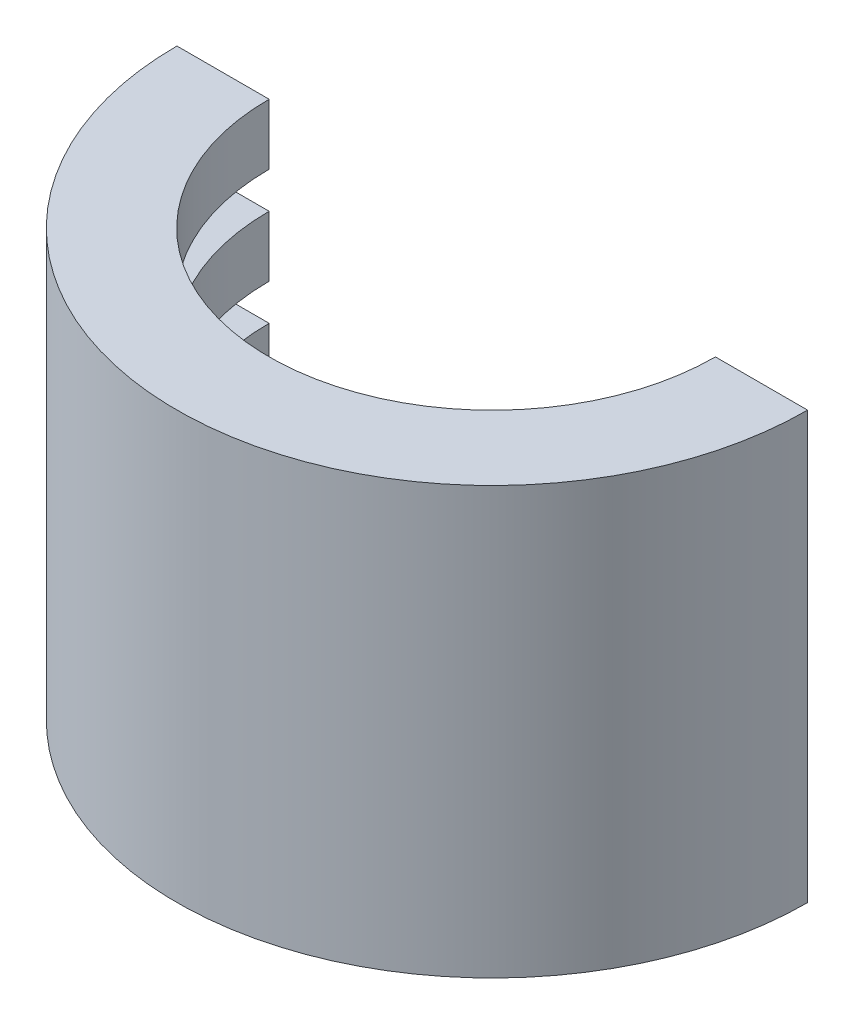
SolidWorks part; units mm, degrees
ref_plane "前视基准面" through (0, 0, 0) normal (0, 0, 1) x (1, 0, 0)
ref_plane "上视基准面" through (0, 0, 0) normal (0, 1, 0) x (1, 0, 0)
ref_plane "右视基准面" through (0, 0, 0) normal (1, 0, 0) x (0, 0, -1)
sketch "草图1" plane through (0, 0, 0) normal (0, 0, 1) x (1, 0, 0)
  line L0 (0, 0) -> (0, 2)
  line L2 (1.5, 2) -> (1.5, 0)
  line L3 (1.5, 0) -> (11, 0)
  line L6 (13, 16) -> (9.2, 16)
  line L7 (9.2, 1.5) -> (9.2, 4)
  line L8 (9.2, 4) -> (11, 4)
  line L9 (11, 4) -> (11, 5.5)
  line L10 (11, 5.5) -> (9.2, 5.5)
  line L11 (9.2, 5.5) -> (9.2, 8)
  line L12 (9.2, 8) -> (11, 8)
  line L13 (11, 8) -> (11, 9.5)
  line L14 (11, 9.5) -> (9.2, 9.5)
  line L15 (9.2, 9.5) -> (9.2, 12)
  line L16 (11, 0) -> (11, 1.5)
  line L17 (9.2, 12) -> (11, 12)
  line L18 (9.2, 1.5) -> (11, 1.5)
  line L19 (11, 12) -> (11, 13.5)
  line L20 (11, 13.5) -> (9.2, 13.5)
  line L21 (9.2, 13.5) -> (9.2, 16)
  line L22 (0, 0) -> (0, -1.5846)
  line L23 (0, -1.5846) -> (13, -1.5846)
  line L25 (13, 16) -> (13, -1.5846)
  line L26 (0, 2) -> (1.5, 2)
  line L27 (7.2, 1.5) -> (7.2, 16)
  line L28 (7.2, 16) -> (13, 16)
  line L29 (13, 18) -> (0, 18)
  line L30 (0, 18) -> (0, 2)
  line L31 (1.5, 2) -> (1.5, 1.5)
  line L32 (0, 2) -> (1.6, 2)
  line L33 (13, 16) -> (13, 18)
  line L34 (1.6, 2) -> (1.6, 1.5)
  line L35 (1.6, 1.5) -> (7.2, 1.5)
  dimension "D1" = 2.5
  dimension "D2" = 1.5
  dimension "D3" = 2
  dimension "D4" = 11
  dimension "D5" = 1.5
  dimension "D6" = 2.5
  dimension "D7" = 1.5
  dimension "D8" = 2.5
  dimension "D9" = 1.5
  dimension "D10" = 1.5
  dimension "D11" = 2.5
  dimension "D12" = 13
  dimension "D13" = 2
  dimension "D14" = 5.7
  dimension "D15" = 1.8
  dimension "D16" = 1.8
  dimension "D17" = 1.8
  dimension "D18" = 1.8
  dimension "D19" = 1.8
  dimension "D20" = 1.8
  dimension "D21" = 1.8
  dimension "D22" = 3.8
  dimension "D23" = 0.5
  dimension "D24" = 1.6
revolve "旋转1" add sketch "草图1" angle 360 about L30
sketch "草图2" plane through (0, 16, 0) normal (0, 1, 0) x (1, 0, 0)
  line L0 (-13, 0) -> (13, 0)
  arc A0 (13, 0) -> (-13, 0) centre (0, 0) ccw
extrude "切除-拉伸1" cut sketch "草图2" against normal blind 20
